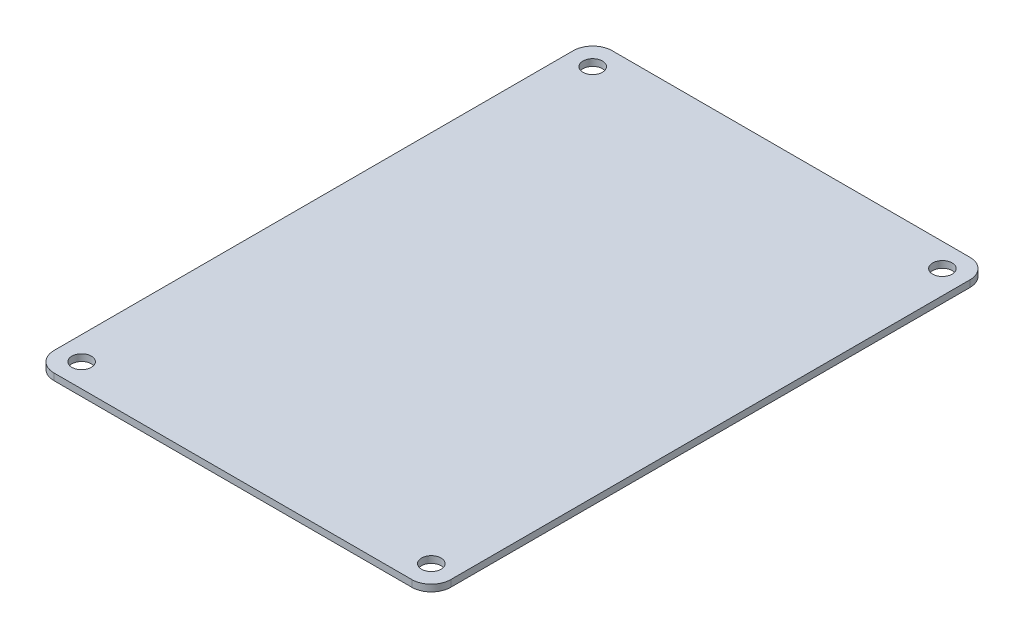
SolidWorks part; units mm, degrees
ref_plane "Front Plane" through (0, 0, 0) normal (0, 0, 1) x (1, 0, 0)
ref_plane "Top Plane" through (0, 0, 0) normal (0, 1, 0) x (1, 0, 0)
ref_plane "Right Plane" through (0, 0, 0) normal (1, 0, 0) x (0, 0, -1)
sketch "Sketch2" plane through (0, 0, 0) normal (0, 1, 0) x (1, 0, 0)
  line L0 (-42.4624, 0) -> (80.3953, 0) construction
  line L1 (-26, 38) -> (26, 38) construction
  line L2 (-26, 38) -> (-26, -38) construction
  line L3 (-26, -38) -> (26, -38) construction
  line L4 (26, 38) -> (26, -38) construction
  line L5 (-29.5, 38.6) -> (-29.5, -38.6)
  line L6 (-26.6, -41.5) -> (26.6, -41.5)
  line L7 (29.5, -38.6) -> (29.5, 38.6)
  line L8 (-26.6, 41.5) -> (26.6, 41.5)
  line L9 (0, 46.4048) -> (0, -52.7831) construction
  circle A0 centre (-26, 38) radius 1.45
  circle A1 centre (26, 38) radius 1.45
  circle A2 centre (26, -38) radius 1.45
  circle A3 centre (-26, -38) radius 1.45
  arc A4 (-29.5, 38.6) -> (-26.6, 41.5) centre (-26.6, 38.6) cw
  arc A5 (26.6, 41.5) -> (29.5, 38.6) centre (26.6, 38.6) cw
  arc A6 (29.5, -38.6) -> (26.6, -41.5) centre (26.6, -38.6) cw
  arc A7 (-26.6, -41.5) -> (-29.5, -38.6) centre (-26.6, -38.6) cw
  point P15 (-26, 0)
  point P16 (0, 38)
  point P27 (0, 41.5)
  point P28 (-29.5, 0)
  dimension "D5" = 2.9
  dimension "D3" = 2.9
  dimension "D1" = 76
  dimension "D2" = 52
  dimension "D4" = 83
  dimension "D6" = 59
extrude "Boss-Extrude1" add sketch "Sketch2" along normal blind 1
